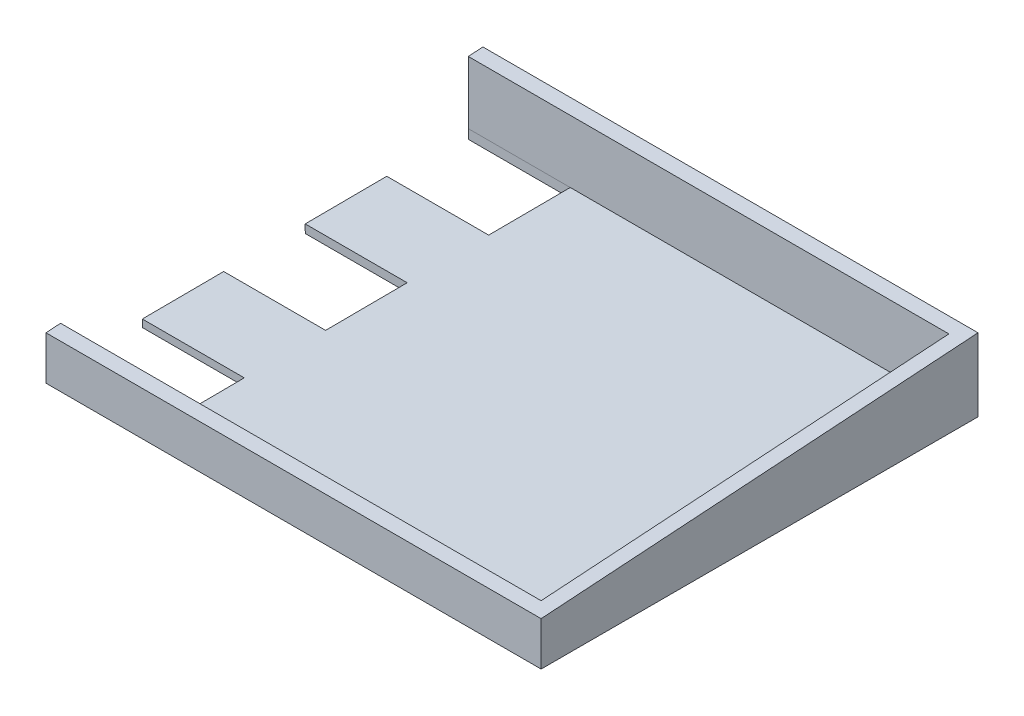
SolidWorks part; units mm, degrees
ref_plane "Front Plane" through (0, 0, 0) normal (0, 0, 1) x (1, 0, 0)
ref_plane "Top Plane" through (0, 0, 0) normal (0, 1, 0) x (1, 0, 0)
ref_plane "Right Plane" through (0, 0, 0) normal (1, 0, 0) x (0, 0, -1)
sketch "Sketch2" plane through (0, 0, 0) normal (1, 0, 0) x (0, 0, -1)
  line L1 (150, 10) -> (150, -15)
  line L2 (150, -15) -> (0, -15)
  line L3 (0, -15) -> (0, 0)
  line L4 (0, 0) -> (150, 10)
  dimension "D1" = 15
  dimension "D2" = 25
  dimension "D3" = 150
extrude "Boss-Extrude1" add sketch "Sketch2" against normal blind 170
sketch "Sketch3" plane through (-170, 0, 0) normal (-1, 0, 0) x (0, 0, 1)
  line L0 (-145, 9.6667) -> (-145, -11.8)
  line L1 (-150, 10) -> (0, 0) construction
  line L2 (-145, -11.8) -> (-5, -12.6)
  line L3 (-5, -12.6) -> (-5, 0.3333)
  line L4 (-5, 0.3333) -> (-145, 9.6667)
  line L5 (0, -15) -> (-150, -15) construction
  line L6 (-150, -15) -> (-150, 10) construction
  dimension "D1" = 3.2
  dimension "D2" = 2.4
  dimension "D3" = 140
  dimension "D4" = 5
extrude "Cut-Extrude1" cut sketch "Sketch3" against normal blind 165
sketch "Sketch5" plane through (0, -12.6282, -0.0722) normal (0, 1, 0.0057) x (1, 0, 0)
  line L1 (-170, 144.9302) -> (-170, 4.9279) construction
  line L2 (-170, 116.9302) -> (-135, 116.9302)
  line L4 (-170, 116.9302) -> (-170, 144.9302)
  line L5 (-170, 144.9302) -> (-135, 144.9302)
  line L6 (-5, 144.9302) -> (-170, 144.9302) construction
  line L7 (-135, 144.9302) -> (-135, 116.9302)
  dimension "D1" = 28
  dimension "D2" = 35
extrude "Cut-Extrude3" cut sketch "Sketch5" against normal through all
sketch "Sketch6" plane through (0, -12.6282, -0.0722) normal (0, 1, 0.0057) x (1, 0, 0)
  line L0 (-170, 88.9302) -> (-135, 88.9302)
  line L1 (-170, 116.9302) -> (-170, 4.9279) construction
  line L2 (-135, 88.9302) -> (-135, 60.9302)
  line L3 (-135, 60.9302) -> (-170, 60.9302)
  line L4 (-170, 116.9302) -> (-135, 116.9302) construction
  line L5 (-170, 88.9302) -> (-170, 60.9302)
  dimension "D1" = 28
  dimension "D2" = 28
  dimension "D3" = 35
extrude "Cut-Extrude5" cut sketch "Sketch6" against normal through all
sketch "Sketch8" plane through (0, -12.6282, -0.0722) normal (0, 1, 0.0057) x (1, 0, 0)
  line L1 (-170, 5.0018) -> (-135, 5.0018)
  line L2 (-170, 5.0018) -> (-170, 33.0018)
  line L3 (-170, 33.0018) -> (-135, 33.0018)
  line L4 (-135, 5.0018) -> (-135, 33.0018)
  dimension "D1" = 35
  dimension "D2" = 28
extrude "Cut-Extrude9" cut sketch "Sketch8" against normal through all
